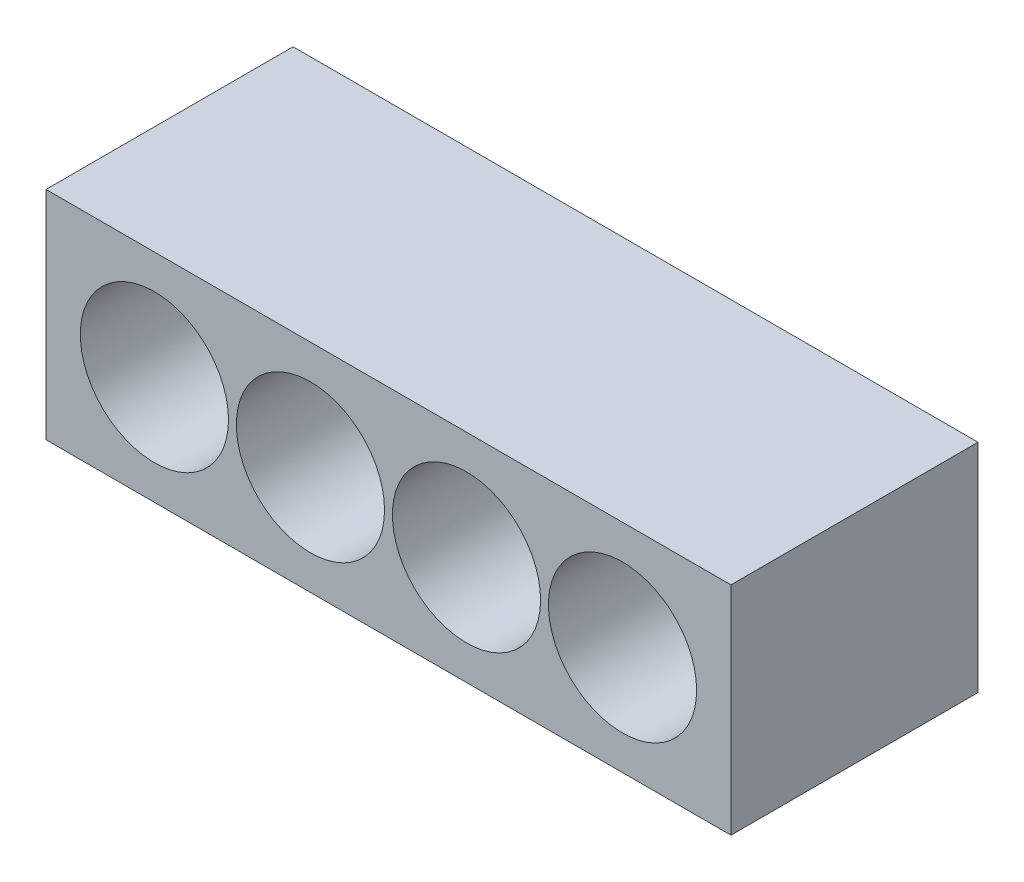
SolidWorks part; units mm, degrees
ref_plane "Front Plane" through (0, 0, 0) normal (0, 0, 1) x (1, 0, 0)
ref_plane "Top Plane" through (0, 0, 0) normal (0, 1, 0) x (1, 0, 0)
ref_plane "Right Plane" through (0, 0, 0) normal (1, 0, 0) x (0, 0, -1)
sketch "Sketch1" plane through (0, 0, 0) normal (0, 0, 1) x (1, 0, 0)
  line L0 (-114.8461, 0) -> (284.3769, 0) construction
  line L1 (-114.8461, 63.1827) -> (284.3769, 63.1827)
  line L2 (-114.8461, 63.1827) -> (-114.8461, -63.1827)
  line L3 (-114.8461, -63.1827) -> (284.3769, -63.1827)
  line L4 (284.3769, 63.1827) -> (284.3769, -63.1827)
  circle A0 centre (-51.6634, 0) radius 43.1827
  circle A1 centre (39.2891, 0) radius 43.1827
  circle A2 centre (130.2416, 0) radius 43.1827
  circle A3 centre (221.1942, 0) radius 43.1827
  dimension "D1" = 20
  dimension "D2" = 20
  dimension "D3" = 20
extrude "Extrude1" add sketch "Sketch1" along normal blind 144
